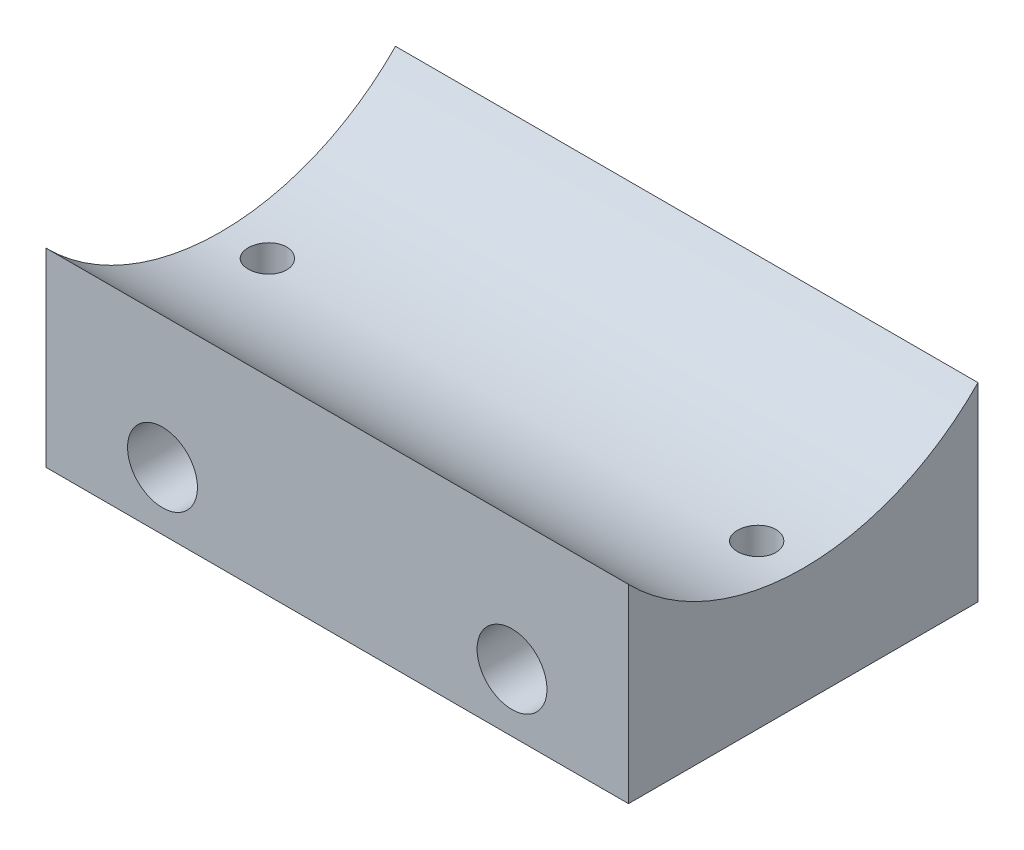
SolidWorks part; units mm, degrees
material "1060 合金"
ref_plane "前视基准面" through (0, 0, 0) normal (0, 0, 1) x (1, 0, 0)
ref_plane "上视基准面" through (0, 0, 0) normal (0, 1, 0) x (1, 0, 0)
ref_plane "右视基准面" through (0, 0, 0) normal (1, 0, 0) x (0, 0, -1)
sketch "草图1" plane through (0, 0, 0) normal (1, 0, 0) x (0, 0, -1)
  line L1 (-15, -31) -> (15, -31)
  line L2 (-15, -31) -> (-15, -14.6969)
  line L3 (-15, -14.6969) -> (15, -14.6969) construction
  line L4 (15, -31) -> (15, -14.6969)
  line L5 (-15, -31) -> (15, -14.6969) construction
  line L6 (-15, -14.6969) -> (15, -31) construction
  arc A0 (-15, -14.6969) -> (15, -14.6969) centre (0, 0) ccw
  point P3 (0, -22.8485)
  dimension "D1" = 42
  dimension "D2" = 10
  dimension "D3" = 30
extrude "凸台-拉伸1" add sketch "草图1" along normal mid plane 50
hole_wizard "Ø6.0 (6) 直径孔1" positions "草图3" profile "草图2" hole size "Ø6.0" standard "GB" end condition up to next
sketch "草图3" plane through (0, 0, -15) normal (0, 0, -1) x (-1, 0, 0)
  line L0 (0, 0) -> (0, -34.767) construction
  line L3 (-25, -31) -> (-25, -14.6969) construction
  line L4 (-25, -31) -> (25, -31) construction
  point P0 (-15, -26)
  point P10 (15, -26)
  dimension "D1" = 10
  dimension "D2" = 5
sketch "草图2" plane through (15, -26, -15) normal (1, 0, 0) x (0, 1, 0)
  line L0 (0, 0) -> (0, 30)
  line L1 (0, 30) -> (3, 30)
  line L2 (3, 30) -> (3, 0)
  line L5 (3, 0) -> (0, 0)
  line L11 (0, -6.35) -> (0, 107.95) construction
  dimension "通孔孔直径" = 6
  dimension "通孔孔深度" = 30
hole_wizard "M4 螺纹孔1" positions "草图5" profile "草图4" tap size "M4" standard "GB" end condition up to next
sketch "草图5" plane through (0, -31, 0) normal (0, -1, 0) x (-1, 0, 0)
  line L0 (0, 0) -> (0, 12.0531) construction
  line L3 (-25, -15) -> (-25, 15) construction
  point P0 (-21, 0)
  point P12 (21, 0)
  dimension "D1" = 4
sketch "草图4" plane through (21, -31, 0) normal (1, 0, 0) x (0, 0, -1)
  line L0 (0, 0) -> (0, 10)
  line L1 (0, 10) -> (1.65, 10)
  line L2 (1.65, 10) -> (1.65, 0)
  line L5 (1.65, 0) -> (0, 0)
  line L11 (0, -6.35) -> (0, 107.95) construction
  dimension "螺纹线主直径" = 3.3
  dimension "通孔螺纹孔钻头深度" = 10
